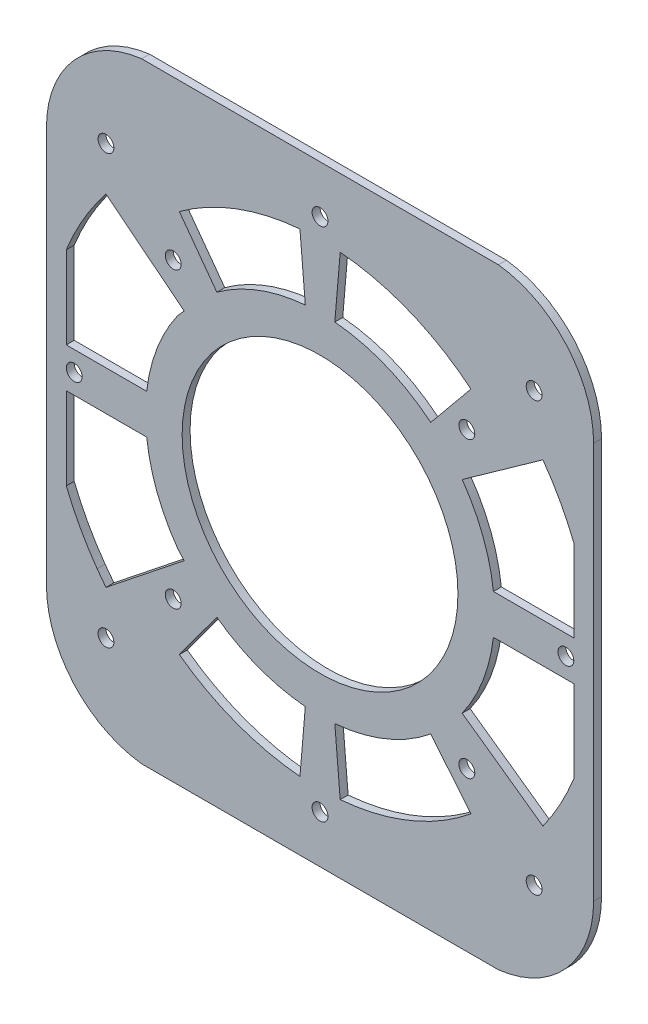
SolidWorks part; units mm, degrees
ref_plane "Front Plane" through (0, 0, 0) normal (0, 0, 1) x (1, 0, 0)
ref_plane "Top Plane" through (0, 0, 0) normal (0, 1, 0) x (1, 0, 0)
ref_plane "Right Plane" through (0, 0, 0) normal (1, 0, 0) x (0, 0, -1)
sketch "Sketch1" plane through (0, 0, 0) normal (0, 0, 1) x (1, 0, 0)
  line L1 (69, -50) -> (-69, -50)
  line L2 (69, -50) -> (69, 50)
  line L3 (69, 50) -> (-69, 50)
  line L4 (-69, -50) -> (-69, 50)
  line L5 (69, -50) -> (-69, 50) construction
  line L6 (69, 50) -> (-69, -50) construction
  line L7 (45, -72) -> (-45, -72)
  line L8 (45, -72) -> (45, 72)
  line L9 (45, 72) -> (-45, 72)
  line L10 (-45, -72) -> (-45, 72)
  line L11 (45, -72) -> (-45, 72) construction
  line L12 (45, 72) -> (-45, -72) construction
  arc A0 (-69, 50) -> (-45, 72) centre (-46.9167, 50) cw
  arc A1 (45, 72) -> (69, 50) centre (45, 47.9091) cw
  arc A2 (69, -50) -> (45, -72) centre (46.9167, -50) cw
  arc A3 (-45, -72) -> (-69, -50) centre (-45, -47.9091) cw
  point P0 (0, 0)
  point P6 (0, 0)
extrude "Boss-Extrude1" add sketch "Sketch1" along normal blind 2 contours L10 L1 L8 L3 | L10 L3 L8 L9 | L8 L1 L2 L3 | A1 L8 L3 | A2 L1 L8 | L10 L7 L8 L1 | A3 L10 L1 | L1 L10 L3 L4 | A0 L3 L10
sketch "Sketch2" plane through (0, 0, 2) normal (0, 0, 1) x (1, 0, 0)
  line L0 (-69, 0) -> (-64, 0)
  line L1 (69, 0) -> (64, 0)
  line L2 (-69, -50) -> (-69, 50) construction
  line L3 (64, 0) -> (64, 25.7876)
  line L4 (64, 25.7876) -> (64, -25.7876)
  line L5 (64, -25.7876) -> (-64, -25.7876)
  line L6 (-64, -25.7876) -> (-64, 25.7876)
  line L7 (-64, 25.7876) -> (64, 25.7876)
  line L8 (0, 60) -> (5.0847, 60)
  line L9 (0, 60) -> (-5.0847, 60)
  line L10 (-5.0847, 60) -> (-5.0847, 43.715)
  line L11 (-5.0847, 43.715) -> (5.0847, 43.715)
  line L12 (5.0847, 43.715) -> (5.0847, 60)
  line L13 (5.0847, 59.7842) -> (38.0593, 46.3842)
  line L14 (38.0593, 46.3842) -> (0, 0)
  line L15 (0, 0) -> (5.0847, 59.7842)
  line L16 (-5.0847, 60) -> (-35.4831, 48.3834)
  line L17 (-35.4831, 48.3834) -> (0, 0)
  line L18 (-5.0847, 60) -> (0, 0)
  line L19 (-69, 0) -> (-56.2174, 40.0076)
  line L20 (-56.2174, 40.0076) -> (0, 0)
  line L21 (0, 0) -> (-64, 0)
  line L22 (0, 72) -> (0, -72)
  line L23 (45, 72) -> (-45, 72) construction
  line L24 (45, -72) -> (-45, -72) construction
  line L25 (0, 0) -> (69, 0)
  line L26 (-69, 0) -> (-56.2174, -40.0076)
  line L27 (-56.2174, -40.0076) -> (0, 0)
  line L28 (-5.0847, -60) -> (0, 0)
  line L29 (-35.4831, -48.3834) -> (0, 0)
  line L30 (-5.0847, -60) -> (-35.4831, -48.3834)
  line L31 (38.0593, -46.3842) -> (0, 0)
  line L32 (0, 0) -> (5.0847, -59.7842)
  line L33 (5.0847, -59.7842) -> (38.0593, -46.3842)
  line L34 (56.2174, -40.0076) -> (0, 0)
  line L35 (69, 0) -> (56.2174, -40.0076)
  line L36 (64, -25.7876) -> (64, 25.7876)
  line L37 (69, 0) -> (56.2174, 40.0076)
  line L38 (56.2174, 40.0076) -> (0, 0)
  line L40 (64, 5) -> (-64, 5)
  line L41 (64, 5) -> (64, -5)
  line L42 (64, -5) -> (-64, -5)
  line L43 (-64, 5) -> (-64, -5)
  line L44 (64, 5) -> (-64, -5) construction
  line L45 (64, -5) -> (-64, 5) construction
  circle A0 centre (0, 0) radius 60
  circle A1 centre (0, 0) radius 69
  circle A2 centre (0, 0) radius 44.0097
extrude "Cut-Extrude1" cut sketch "Sketch2" against normal blind 10 contours A2 L14 L13 L12 | L13 A0 | A2 L12 L15 | A2 L18 A0 L10 | A2 L10 A0 L16 L17 | L16 A0 | L19 A1 L7 | A0 L20 L19 L7 | L20 A0 L7 | A2 L20 L7 A0 L40 | A0 L7 L19 L6 L40 | A2 L42 A0 L5 L27 | A0 L42 L6 L26 L5 | L26 L6 L5 | L5 A1 L26 | A0 L5 L26 L27 | L5 A0 L27 | A2 L32 L33 L31 | A2 L29 L30 A0 L28 | L30 A0 | L33 A0 | A0 L34 L35 L5 | L34 A0 L5 | L35 A1 L5 | L4 L35 L5 | A0 L5 L35 L36 L42 | A2 L34 L5 A0 L42 | A0 L40 L36 L37 L7 | A0 L7 L37 L38 | L7 A0 L38 | A2 L40 A0 L7 L38 | L7 A1 L37 | L37 L36 L7
sketch "Sketch3" plane through (0, 0, 2) normal (0, 0, 1) x (1, 0, 0)
  line L0 (-64, 25.7876) -> (-64, 15.6492)
  line L1 (-64, 15.6492) -> (-60.7607, 25.7876)
  line L2 (-60.7607, 25.7876) -> (-64, 25.7876)
extrude "Cut-Extrude2" cut sketch "Sketch3" against normal blind 10
sketch "Sketch4" plane through (0, 0, 0) normal (0, 0, -1) x (-1, 0, 0)
  circle A0 centre (0, 0) radius 30
extrude "Cut-Extrude3" cut sketch "Sketch4" against normal blind 10
sketch "Sketch6" plane through (0, 0, 2) normal (0, 0, 1) x (1, 0, 0)
  line L0 (-56.2174, -40.0076) -> (56.2174, -40.0076)
  line L1 (56.2174, -40.0076) -> (56.2174, 40.0076)
  line L2 (56.2174, 40.0076) -> (-56.2174, 40.0076)
  line L3 (-56.2174, 40.0076) -> (-56.2174, -40.0076)
  line L4 (27.9163, -34.0226) -> (35.8567, -25.5177)
  line L5 (-26.0267, -35.489) -> (-34.2574, -27.2582)
  line L6 (0, 0) -> (-34.2574, -27.2582)
  line L7 (-34.2574, -27.2582) -> (-53.9933, -42.9619)
  line L8 (-53.9933, -42.9619) -> (-56.2174, -40.0076)
  line L9 (-35.8567, -25.5177) -> (-34.2574, -27.2582)
  line L10 (-69, 0) -> (69, 0)
  line L11 (-35.8567, 25.5177) -> (-34.2574, 27.2582)
  line L12 (-53.9933, 42.9619) -> (-56.2174, 40.0076)
  line L13 (-34.2574, 27.2582) -> (-53.9933, 42.9619)
  circle A0 centre (0, 0) radius 69
  line M9 (-56.2174, 40.0076) -> (-35.8567, 25.5177)
  line M37 (-35.8567, -25.5177) -> (-56.2174, -40.0076)
extrude "Cut-Extrude4" cut sketch "Sketch6" against normal blind 10 contours L9 L0 L7 M37 | L11 L13 L2 M9 | L8 L7 L0 | L2 L13 L12
sketch "Sketch7" plane through (0, 0, 2) normal (0, 0, 1) x (1, 0, 0)
  line L4 (-26.2247, 19.5306) -> (-18.4877, 25.8662)
  line L5 (-34.2574, 27.2582) -> (-26.0267, 35.489)
  line L6 (-26.2247, 19.5306) -> (-32.5603, 27.2676)
  line L7 (38.0593, 46.3842) -> (27.9163, 34.0226) construction
  line L8 (27.9163, 34.0226) -> (35.8567, 25.5177)
  line L9 (-18.4877, 25.8662) -> (-24.8233, 33.6031)
  line L10 (35.8567, -25.5177) -> (27.9163, -34.0226)
  line L11 (-32.5603, 27.2676) -> (-24.8233, 33.6031)
  line L12 (-26.0267, -35.489) -> (-34.2574, -27.2582)
  line L15 (27.8278, 32.1554) -> (33.9427, 24.2429)
  line L16 (27.8278, 32.1554) -> (19.9153, 26.0405)
  line L17 (33.9427, 24.2429) -> (26.0302, 18.128)
  line L18 (19.9153, 26.0405) -> (26.0302, 18.128)
  line L21 (33.9883, -25.5491) -> (26.5216, -32.201)
  line L22 (33.9883, -25.5491) -> (27.3364, -18.0824)
  line L23 (26.5216, -32.201) -> (19.8697, -24.7343)
  line L24 (27.3364, -18.0824) -> (19.8697, -24.7343)
  line L27 (-26.1267, -33.6122) -> (-32.5693, -25.9642)
  line L28 (-26.1267, -33.6122) -> (-18.4787, -27.1696)
  line L29 (-32.5693, -25.9642) -> (-24.9213, -19.5215)
  line L30 (-18.4787, -27.1696) -> (-24.9213, -19.5215)
  arc A4 (27.9163, 34.0226) -> (3.7296, 43.8514) centre (0, 0) ccw construction
extrude "Cut-Extrude5" cut sketch "Sketch7" against normal blind 10 contours L11 L6 L4 L9 | L16 L18 L17 L15 | L22 L24 L23 L21 | L28 L30 L29 L27
sketch "Sketch8" plane through (0, 0, 2) normal (0, 0, 1) x (1, 0, 0)
  circle A0 centre (0, 0) radius 28
  circle A1 centre (0, 0) radius 30
extrude "Boss-Extrude3" add sketch "Sketch8" against normal blind 2
sketch "Sketch9" plane through (0, 0, 0) normal (0, 0, -1) x (-1, 0, 0)
  line L0 (0, 72) -> (0, 77)
  line L1 (-45, 72) -> (45, 72) construction
  line L2 (0, 77) -> (-45, 77)
  line L3 (-45, 77) -> (45, 77)
  line L4 (69, 50) -> (69, -50)
  line L5 (45, -77) -> (-45, -77)
  line L6 (69, -50) -> (-69, -50)
  line L7 (0, -72) -> (0, -77)
  line L8 (-45, -72) -> (45, -72) construction
  line L9 (-69, -50) -> (-69, 50)
  line L10 (-69, 50) -> (69, 50)
  line L11 (45, 72) -> (45, -72)
  line L12 (45, -72) -> (-45, -72)
  line L13 (-45, -72) -> (-45, 72)
  line L14 (-45, 72) -> (45, 72)
  line L15 (24.8233, 33.6031) -> (18.4877, 25.8662)
  line L16 (24.8233, 33.6031) -> (32.6949, 27.1573)
  line L17 (18.4877, 25.8662) -> (26.3593, 19.4204)
  line L18 (32.6949, 27.1573) -> (26.3593, 19.4204)
  line L19 (24.9213, -19.5215) -> (18.4787, -27.1696)
  line L20 (24.9213, -19.5215) -> (32.5476, -25.9459)
  line L21 (18.4787, -27.1696) -> (26.105, -33.5939)
  line L22 (32.5476, -25.9459) -> (26.105, -33.5939)
  line L23 (-27.3364, -18.0824) -> (-19.8697, -24.7343)
  line L24 (-27.3364, -18.0824) -> (-34.0467, -25.6146)
  line L25 (-19.8697, -24.7343) -> (-26.58, -32.2666)
  line L26 (-34.0467, -25.6146) -> (-26.58, -32.2666)
  line L27 (-33.9427, 24.2429) -> (-26.0302, 18.128)
  line L28 (-33.9427, 24.2429) -> (-27.8292, 32.1535)
  line L29 (-26.0302, 18.128) -> (-19.9167, 26.0386)
  line L30 (-27.8292, 32.1535) -> (-19.9167, 26.0386)
  arc A0 (69, 50) -> (45, 77) centre (41.8125, 50) ccw
  arc A1 (-69, 50) -> (-45, 77) centre (-41.8125, 50) cw
  arc A2 (-69, -50) -> (-45, -77) centre (-41.8125, -50) ccw
  arc A3 (69, -50) -> (45, -77) centre (41.8125, -50) cw
  arc A4 (45, 72) -> (69, 50) centre (45, 47.9091) cw
  arc A5 (45, -72) -> (69, -50) centre (45, -47.9091) ccw
  arc A6 (-45, -72) -> (-69, -50) centre (-45, -47.9091) cw
  arc A7 (-45, 72) -> (-69, 50) centre (-45, 47.9091) ccw
extrude "Boss-Extrude5" add sketch "Sketch9" against normal up to surface (2 mm away) contours L18 L16 L15 L17 | L22 L20 L19 L21 | L24 L26 L25 L23 | L30 L28 L27 L29 | A7 L14 L0 L2 A1 | L14 A4 A0 L3 L0 | A5 L12 L7 L5 A3 | L12 A6 A2 L5 L7 up to face at (-25.524, -26.5669, 2)
sketch "Sketch10" plane through (0, 0, 0) normal (0, 0, -1) x (-1, 0, 0)
  line L0 (-27.8292, 32.1535) -> (-27.8278, 32.1554)
  line L1 (-27.8292, 32.1535) -> (-19.9167, 26.0386)
  line L2 (-27.8278, 32.1554) -> (-19.9153, 26.0405)
  line L3 (-19.9167, 26.0386) -> (-19.9153, 26.0405)
  line L4 (26.105, -33.5939) -> (26.1267, -33.6122)
  line L5 (26.105, -33.5939) -> (32.5472, -25.9464)
  line L6 (26.1267, -33.6122) -> (32.5689, -25.9647)
  line L7 (32.5472, -25.9464) -> (32.5689, -25.9647)
extrude "Boss-Extrude6" add sketch "Sketch10" against normal up to surface (2 mm away) up to face at (0, 0, 2)
sketch "Sketch11" plane through (0, 0, 0) normal (0, 0, -1) x (-1, 0, 0)
  line L0 (34.2574, 27.2582) -> (0, 0)
  line L1 (34.2574, 27.2582) -> (27.2148, 21.6545)
  circle A0 centre (0, 0) radius 34.7788
  circle A1 centre (0, 0) radius 28
extrude "Cut-Extrude6" cut sketch "Sketch11" against normal blind 10
sketch "Sketch12" plane through (0, 0, 2) normal (0, 0, 1) x (1, 0, 0)
  line L0 (0, 0) -> (0, -65)
  line L1 (0, 0) -> (62, 0)
  line L2 (0, 0) -> (-62, 0)
  line L3 (0, 0) -> (0, 65)
  line L4 (-54, 54) -> (-37.0294, 37.0294)
  line L9 (-54, -54) -> (54, 54) construction
  line L10 (-54, 54) -> (54, -54) construction
  line L11 (0, 77) -> (0, 74)
  line L16 (37.0294, -37.0294) -> (-37.0294, 37.0294) construction
  line L17 (37.0294, 37.0294) -> (-37.0294, -37.0294) construction
  line L18 (-45, 77) -> (45, 77) construction
  line L19 (0, -77) -> (0, -74)
  line L20 (-45, -77) -> (45, -77) construction
  circle A0 centre (-62, 0) radius 2
  circle A1 centre (0, 65) radius 2
  circle A2 centre (0, -65) radius 2
  circle A3 centre (62, 0) radius 2
  circle A4 centre (-54, 54) radius 2
  circle A5 centre (54, 54) radius 2
  circle A6 centre (37.0294, 37.0294) radius 2
  circle A7 centre (-37.0294, 37.0294) radius 2
  circle A8 centre (-54, -54) radius 2
  circle A9 centre (-37.0294, -37.0294) radius 2
  circle A10 centre (37.0294, -37.0294) radius 2
  circle A11 centre (54, -54) radius 2
extrude "Cut-Extrude7" cut sketch "Sketch12" against normal blind 10
